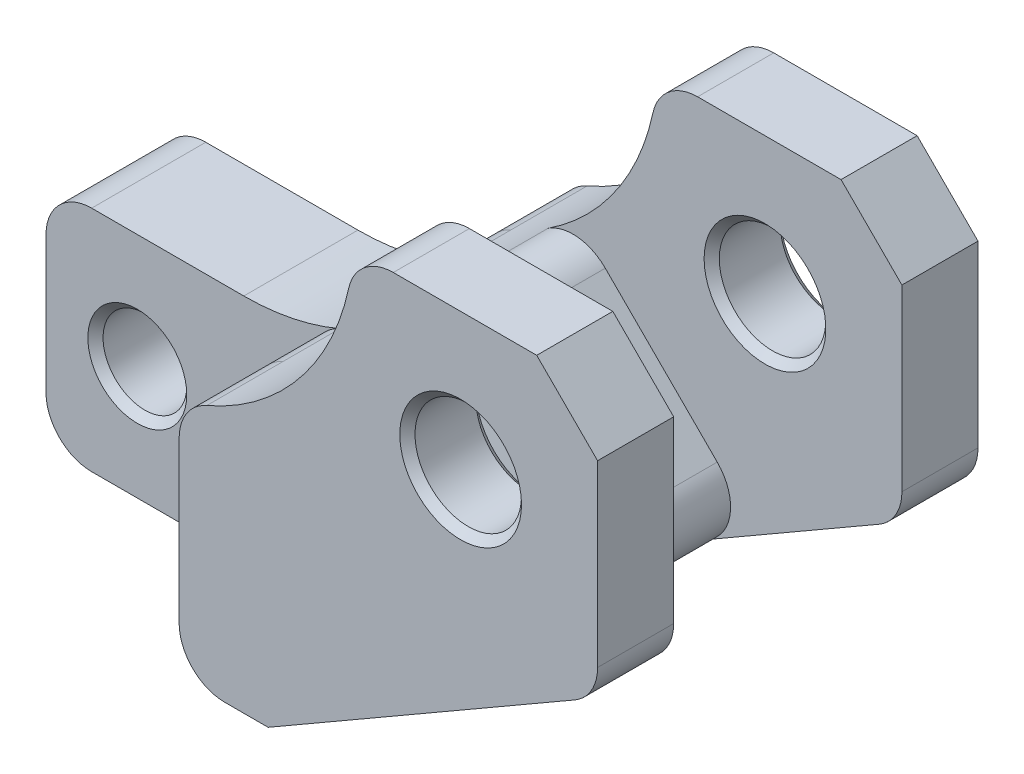
SolidWorks part; units mm, degrees
ref_plane "Płaszczyzna przednia" through (0, 0, 0) normal (0, 0, 1) x (1, 0, 0)
ref_plane "Płaszczyzna górna" through (0, 0, 0) normal (0, 1, 0) x (1, 0, 0)
ref_plane "Płaszczyzna prawa" through (0, 0, 0) normal (1, 0, 0) x (0, 0, -1)
sketch "Sketch1" plane through (0, 0, 0) normal (0, 0, 1) x (1, 0, 0)
  line L0 (0, 0) -> (60.3868, 0) construction
  line L1 (0, 0) -> (0, 45.2976) construction
  line L2 (-12, 15) -> (-12, -15)
  line L3 (-12, -15) -> (34.6987, -15)
  line L4 (34.6987, -15) -> (78, 10)
  line L5 (78, 10) -> (78, 37)
  line L6 (78, 37) -> (70, 45)
  line L7 (70, 45) -> (45.9374, 45)
  line L8 (-12, 15) -> (14, 15)
  arc A0 (14, 15) -> (45.9374, 45) centre (14, 47) ccw
  dimension "D9" = 32
  dimension "D1" = 30
  dimension "D2" = 15
  dimension "D3" = 12
  dimension "D4" = 30
  dimension "D5" = 45
  dimension "D6" = 8
  dimension "D7" = 90
  dimension "D8" = 26
  dimension "D10" = 25
  dimension "D11" = 60
sketch "Sketch2" plane through (0, 0, 0) normal (0, 0, 1) x (1, 0, 0)
  line L0 (-12, 15) -> (14, 15)
  line L6 (-12, 15) -> (-12, -15)
  line L7 (-12, -15) -> (34.6987, -15)
  line L8 (34.6987, -15) -> (55.668, -2.8934)
  line L9 (34.6987, -15) -> (78, 10) construction
  line L10 (55.668, -2.8934) -> (32.1378, 20.6368)
  line L11 (78, 37) -> (70, 45) construction
  arc A0 (14, 15) -> (45.9374, 45) centre (14, 47) ccw construction
  arc A1 (14, 15) -> (32.1378, 20.6368) centre (14, 47) ccw
  dimension "D1" = 44
ref_plane "Plane1" through (0, 0, 15) normal (0, 0, 1) x (1, 0, 0)
sketch "Sketch3" plane through (0, 0, 15) normal (0, 0, 1) x (1, 0, 0)
  line L0 (45.9374, 45) -> (70, 45)
  line L1 (70, 45) -> (78, 37)
  line L2 (78, 37) -> (78, 10)
  line L3 (78, 10) -> (34.6987, -15)
  line L4 (34.6987, -15) -> (23, -15)
  line L5 (-12, -15) -> (34.6987, -15) construction
  line L6 (23, -15) -> (23, 16.2917)
  line L7 (-12, 15) -> (-12, -15) construction
  arc A0 (14, 15) -> (45.9374, 45) centre (14, 47) ccw construction
  arc A1 (23, 16.2917) -> (45.9374, 45) centre (14, 47) ccw
  point P19 (23, 0.6458)
  dimension "D1" = 35
extrude "Boss-Extrude1" add sketch "Sketch3" along normal blind 10
fillet "Fillet1" radius 6 1 edges at (45.9374, 45, 20)
fillet "Fillet2" radius 6 1 edges at (23, -15, 20)
fillet "Fillet3" radius 6 2 edges at (78, 10, 20) (23, 16.2917, 20)
sketch "Sketch4" plane through (0, 0, 25) normal (0, 0, 1) x (1, 0, 0)
  line L0 (70, 45) -> (45.9374, 45) construction
  line L1 (78, 10) -> (78, 37) construction
  circle A0 centre (60, 27) radius 7
  dimension "D3" = 14
  dimension "D1" = 18
  dimension "D2" = 18
extrude "Cut-Extrude1" cut sketch "Sketch4" against normal up to next
chamfer "Chamfer1" distance 1 angle 45 1 edges at (67, 27, 25)
chamfer "Chamfer2" distance 1 angle 45 1 edges at (67, 27, 15)
extrude "Boss-Extrude2" add sketch "Sketch2" along normal mid plane 15 separate body
fillet "Fillet4" radius 6 4 edges at (55.668, -2.8934, 0) (32.1378, 20.6368, 0) (-12, -15, 0) (-12, 15, 0)
sketch "Sketch5" plane through (0, 0, 7.5) normal (0, 0, 1) x (1, 0, 0)
  circle A0 centre (0, 0) radius 5.5
  dimension "D1" = 11
extrude "Cut-Extrude2" cut sketch "Sketch5" against normal up to next (15 mm away)
chamfer "Chamfer3" distance 1 angle 45 2 edges at (5.5, 0, -7.5) (5.5, 0, 7.5)
sketch "Sketch6" plane through (0, 0, 0) normal (0, 0, 1) x (1, 0, 0)
  line L0 (23, -15) -> (23, 16.2917)
  line L1 (-12, -15) -> (34.6987, -15) construction
  line L2 (23, -15) -> (34.6987, -15)
  line L3 (34.6987, -15) -> (59.2543, -0.8228)
  line L4 (34.6987, -15) -> (78, 10) construction
  line L5 (59.2543, -0.8228) -> (35.3067, 23.1248)
  line L7 (78, 37) -> (70, 45) construction
  line L8 (-12, 15) -> (-12, -15) construction
  arc A0 (14, 15) -> (45.9374, 45) centre (14, 47) ccw construction
  arc A1 (23, 16.2917) -> (35.3067, 23.1248) centre (14, 47) ccw
  point P17 (74, 41)
  dimension "D1" = 40
  dimension "D2" = 35
extrude "Boss-Extrude3" add sketch "Sketch6" along normal mid plane 30
fillet "Fillet5" radius 6 6 edges at (23, -15, -11.25) (23, -15, 11.25) (23, 16.2917, -11.25) (23, 16.2917, 11.25) (59.2543, -0.8228, 0) (35.3067, 23.1248, 0)
mirror "Mirror16" about plane through (0, 0, 0) normal (0, 0, 1) of "Boss-Extrude1", "Fillet1", "Fillet2", "Fillet3", "Cut-Extrude1", "Chamfer1", "Chamfer2"
